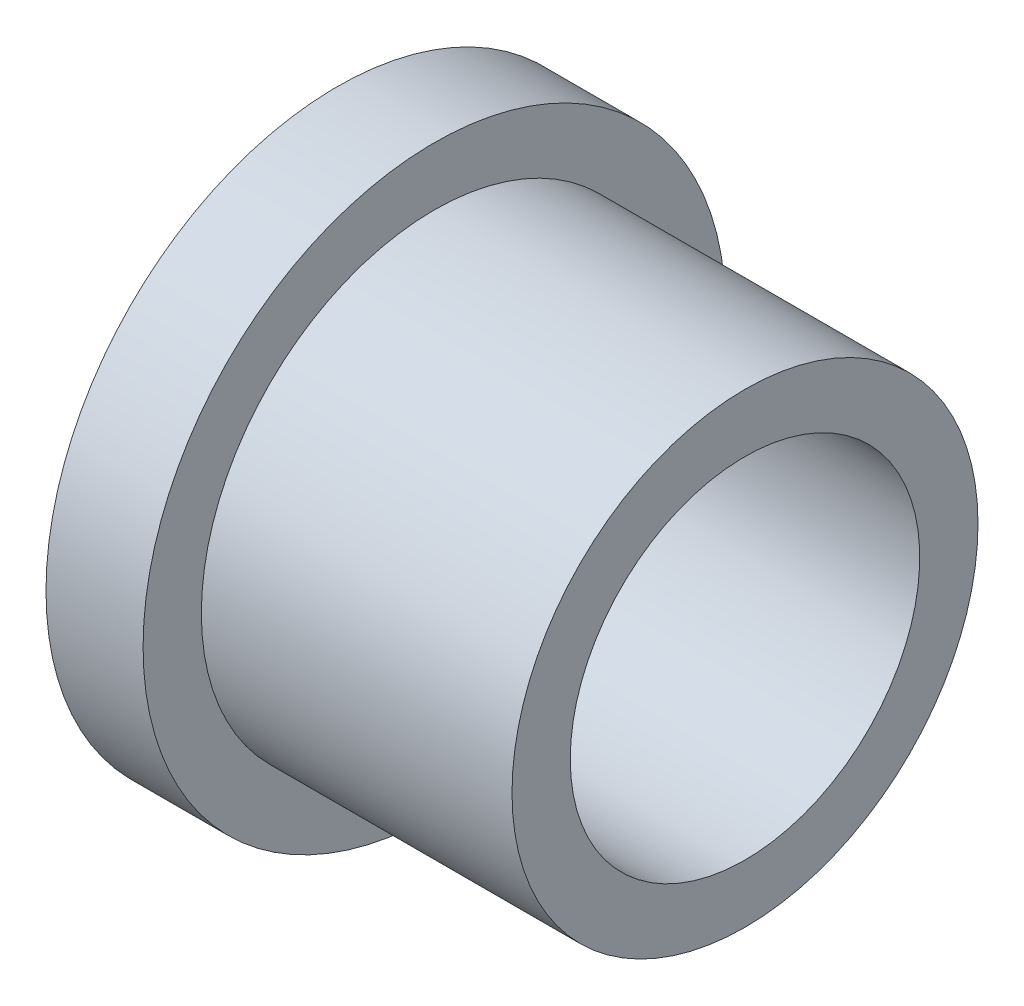
SolidWorks part; units mm, degrees
ref_plane "Front Plane" through (0, 0, 0) normal (0, 0, 1) x (1, 0, 0)
ref_plane "Top Plane" through (0, 0, 0) normal (0, 1, 0) x (1, 0, 0)
ref_plane "Right Plane" through (0, 0, 0) normal (1, 0, 0) x (0, 0, -1)
sketch "Sketch1" plane through (0, 0, 0) normal (0, 0, 1) x (1, 0, 0)
  line L0 (-10.5, 0) -> (63.4619, 0)
  line L1 (-10.5, 9) -> (-10.5, 15)
  line L2 (-10.5, 15) -> (-5.5, 15)
  line L3 (-5.5, 15) -> (-5.5, 12)
  line L4 (-5.5, 12) -> (10.5, 12)
  line L5 (10.5, 12) -> (10.5, 9)
  line L6 (10.5, 9) -> (-5.5, 9)
  line L7 (-10.5, 0) -> (0, 0)
  line L8 (-5.5, 9) -> (-5.5, 12)
  line L9 (-5.5, 9) -> (-5.5, 0)
  line L10 (-10.5, 9) -> (-5.5, 9)
  dimension "D2" = 5
  dimension "D1" = 15
  dimension "D3" = 3
  dimension "D4" = 16
  dimension "D5" = 3
  dimension "D6" = 21
  dimension "D7" = 10.5
revolve "Revolve1" add sketch "Sketch1" angle 360 about L0
